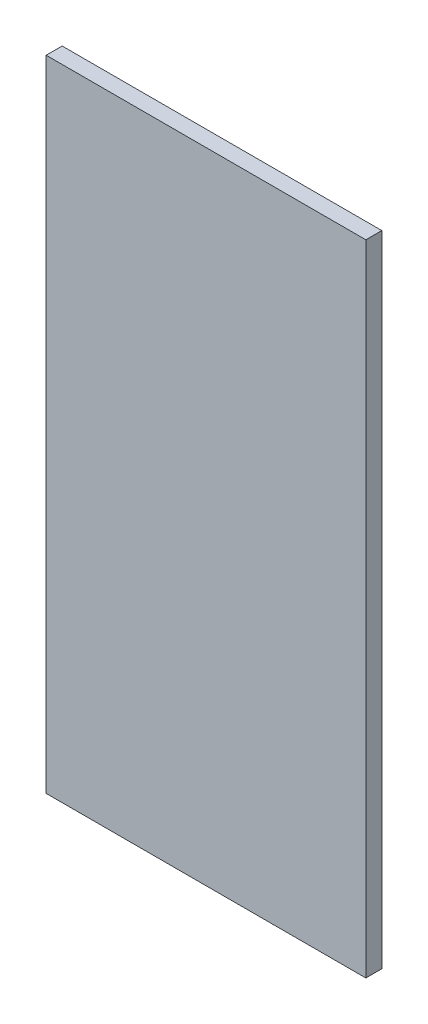
SolidWorks part; units mm, degrees
ref_plane "정면" through (0, 0, 0) normal (0, 0, 1) x (1, 0, 0)
ref_plane "윗면" through (0, 0, 0) normal (0, 1, 0) x (1, 0, 0)
ref_plane "우측면" through (0, 0, 0) normal (1, 0, 0) x (0, 0, -1)
sketch "스케치1" plane through (0, 0, 0) normal (0, 0, 1) x (1, 0, 0)
  line L1 (0, 0) -> (100, 0)
  line L2 (0, 0) -> (0, 200)
  line L3 (0, 200) -> (100, 200)
  line L4 (100, 0) -> (100, 200)
  dimension "D1" = 100
  dimension "D2" = 200
extrude "보스-돌출1" add sketch "스케치1" along normal blind 5
